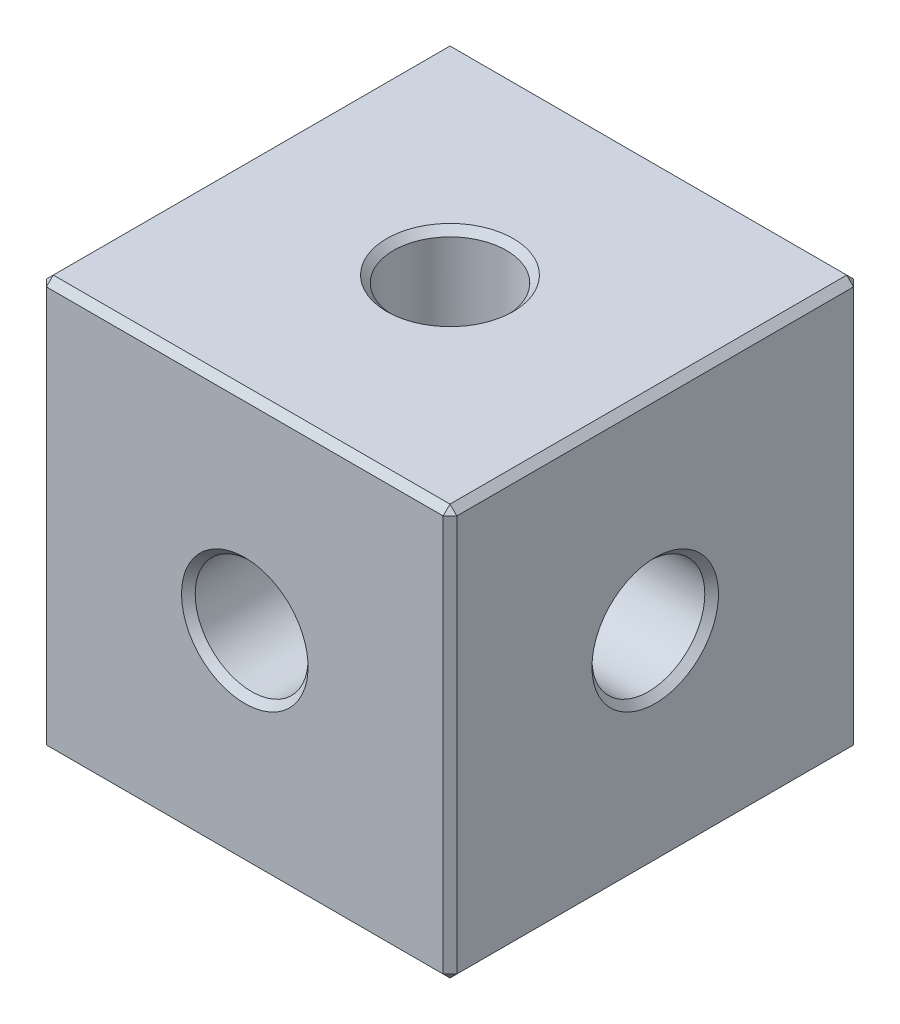
SolidWorks part; units mm, degrees
ref_plane "前视基准面" through (0, 0, 0) normal (0, 0, 1) x (1, 0, 0)
ref_plane "上视基准面" through (0, 0, 0) normal (0, 1, 0) x (1, 0, 0)
ref_plane "右视基准面" through (0, 0, 0) normal (1, 0, 0) x (0, 0, -1)
sketch "草图1" plane through (0, 0, 0) normal (0, 1, 0) x (1, 0, 0)
  line L1 (-6, 6) -> (6, 6)
  line L2 (-6, 6) -> (-6, -6)
  line L3 (-6, -6) -> (6, -6)
  line L4 (6, 6) -> (6, -6)
  line L5 (-6, 6) -> (6, -6) construction
  line L6 (-6, -6) -> (6, 6) construction
  point P0 (0, 0)
  dimension "D1" = 12
extrude "凸台-拉伸1" add sketch "草图1" along normal mid plane 12
hole_wizard "M4 螺纹孔1" positions "草图2" profile "草图3" tap size "M4" standard "GB" end condition through all
sketch "草图2" plane through (0, 0, 6) normal (0, 0, 1) x (1, 0, 0)
  point P0 (0, 0)
sketch "草图3" plane through (0, 0, 6) normal (1, 0, 0) x (0, -1, 0)
  line L0 (0, 0) -> (0, 12)
  line L1 (0, 12) -> (1.65, 12)
  line L2 (1.65, 12) -> (1.65, 0)
  line L5 (1.65, 0) -> (0, 0)
  line L11 (0, -6.35) -> (0, 107.95) construction
  dimension "通孔螺纹孔钻头直径" = 3.3
  dimension "通孔螺纹孔钻头深度" = 12
cosmetic thread "孔螺蚊线1"
hole_wizard "M4 螺纹孔2" positions "草图4" profile "草图5" tap size "M4" standard "GB" end condition through all
sketch "草图4" plane through (0, 6, 0) normal (0, 1, 0) x (1, 0, 0)
  point P0 (0, 0)
sketch "草图5" plane through (0, 6, 0) normal (1, 0, 0) x (0, 0, 1)
  line L0 (0, 0) -> (0, 12)
  line L1 (0, 12) -> (1.65, 12)
  line L2 (1.65, 12) -> (1.65, 0)
  line L5 (1.65, 0) -> (0, 0)
  line L11 (0, -6.35) -> (0, 107.95) construction
  dimension "通孔螺纹孔钻头直径" = 3.3
  dimension "通孔螺纹孔钻头深度" = 12
cosmetic thread "孔螺蚊线2" parameters "D2"=4
hole_wizard "M4 螺纹孔3" positions "草图6" profile "草图7" tap size "M4" standard "GB" end condition through all
sketch "草图6" plane through (6, 0, 0) normal (1, 0, 0) x (0, 0, -1)
  point P0 (0, 0)
sketch "草图7" plane through (6, 0, 0) normal (0, 1, 0) x (0, 0, -1)
  line L0 (0, 0) -> (0, 12)
  line L1 (0, 12) -> (1.65, 12)
  line L2 (1.65, 12) -> (1.65, 0)
  line L5 (1.65, 0) -> (0, 0)
  line L11 (0, -6.35) -> (0, 107.95) construction
  dimension "通孔螺纹孔钻头直径" = 3.3
  dimension "通孔螺纹孔钻头深度" = 12
cosmetic thread "孔螺蚊线3"
chamfer "倒角1" distance 0.2 angle 45 18 edges at (0, -6, 1.65) (-6, 0, -1.65) (1.65, 0, -6) (6, 0, -1.65) (1.65, 0, 6) (-6, -6, 0) (-6, 0, -6) (0, -6, -6) (6, 0, -6) (6, -6, 0) (-6, 0, 6) (0, -6, 6) (6, 0, 6) (0, 6, 6) (-6, 6, 0) (0, 6, -6) (6, 6, 0) (0, 6, 1.65)
